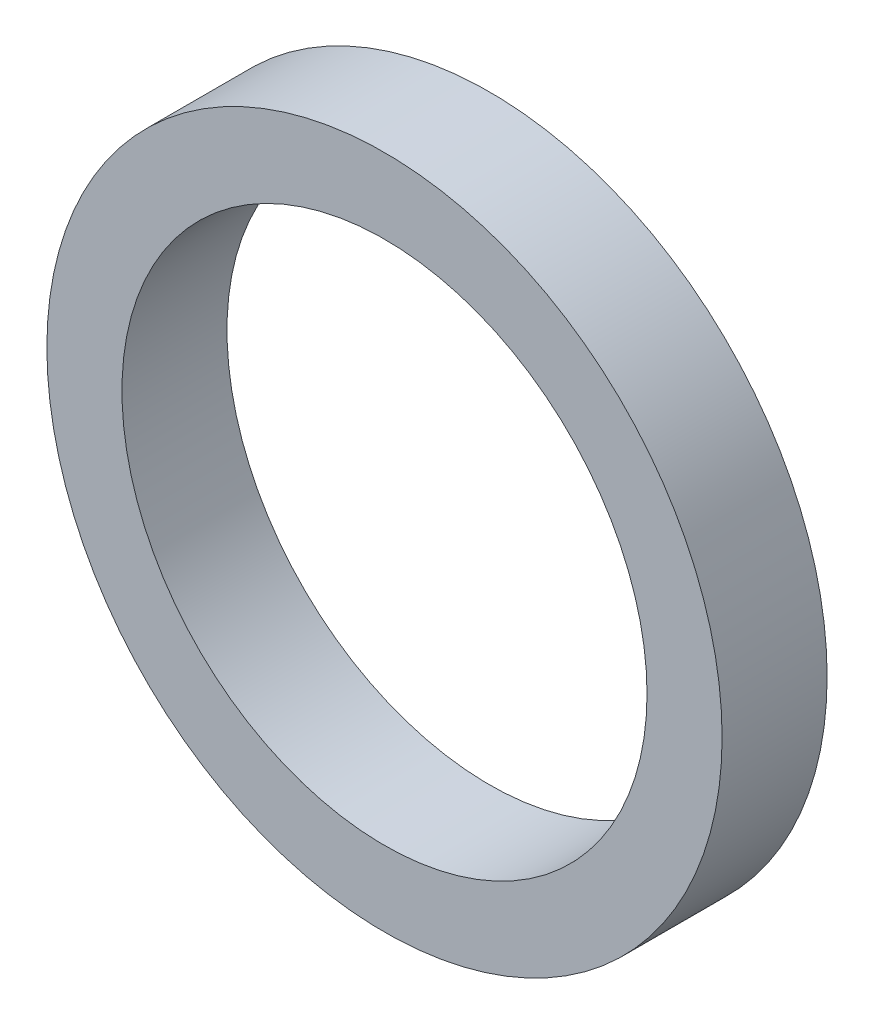
SolidWorks part; units mm, degrees
ref_plane "Piano frontale" through (0, 0, 0) normal (0, 0, 1) x (1, 0, 0)
ref_plane "Piano superiore" through (0, 0, 0) normal (0, 1, 0) x (1, 0, 0)
ref_plane "Piano destro" through (0, 0, 0) normal (1, 0, 0) x (0, 0, -1)
sketch "Schizzo1" plane through (0, 0, 0) normal (0, 0, 1) x (1, 0, 0)
  circle A0 centre (0, 0) radius 2.5
  circle A1 centre (0, 0) radius 3.215
  dimension "D1" = 5
  dimension "D2" = 6.43
extrude "Estrusione-Estrusione1" add sketch "Schizzo1" along normal blind 1
